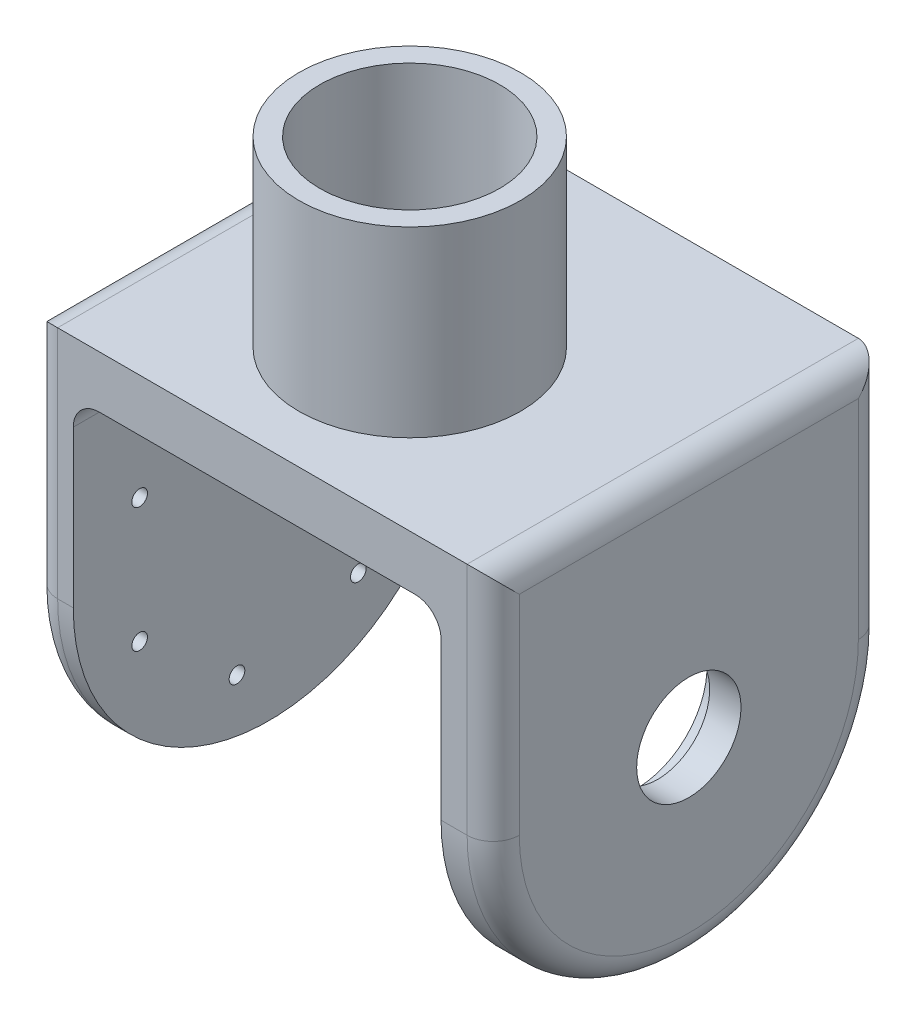
SolidWorks part; units mm, degrees
ref_plane "Alzado" through (0, 0, 0) normal (0, 0, 1) x (1, 0, 0)
ref_plane "Planta" through (0, 0, 0) normal (0, 1, 0) x (1, 0, 0)
ref_plane "Vista lateral" through (0, 0, 0) normal (1, 0, 0) x (0, 0, -1)
sketch "Croquis1" plane through (0, 0, 0) normal (1, 0, 0) x (0, 0, -1)
  line L0 (-37.5, 0) -> (-37.5, 45)
  line L1 (-37.5, 45) -> (37.5, 45)
  line L2 (37.5, 45) -> (37.5, 0)
  arc A0 (-37.5, 0) -> (37.5, 0) centre (0, 0) ccw
  circle A1 centre (27.5, 0) radius 1.5
  circle A2 centre (17.146, -21.5004) radius 1.5
  circle A3 centre (-6.1193, -26.8105) radius 1.5
  circle A4 centre (-24.7766, -11.9318) radius 1.5
  circle A5 centre (-24.7766, 11.9318) radius 1.5
  circle A6 centre (-6.1193, 26.8105) radius 1.5
  circle A7 centre (17.146, 21.5004) radius 1.5
  point P19 (0, 0)
  dimension "D1" = 75
  dimension "D2" = 3
  dimension "D3" = 27.5
  dimension "D5" = 45
  dimension "D4" = 7
extrude "Saliente-Extruir1" add sketch "Croquis1" along normal blind 8
sketch "Croquis2" plane through (0, 0, 0) normal (1, 0, 0) x (0, 0, -1)
  line L10 (37.5, 0) -> (37.5, 45) construction
  line L11 (-37.5, 45) -> (37.5, 45)
  line L12 (-37.5, 45) -> (-37.5, 35)
  line L13 (-37.5, 35) -> (37.5, 35)
  line L14 (37.5, 45) -> (37.5, 35)
  dimension "D1" = 10
extrude "Saliente-Extruir2" add sketch "Croquis2" along normal blind 78.5
ref_plane "Plano1" through (0, 80, 0) normal (0, 1, 0) x (1, 0, 0)
sketch "Croquis6" plane through (0, 80, 0) normal (0, 1, 0) x (1, 0, 0)
  circle A0 centre (42, 0) radius 6 construction
  circle A1 centre (42, -7) radius 17.25
  circle A2 centre (42, -7) radius 21.25
  dimension "D1" = 12
  dimension "D2" = 34.5
  dimension "D3" = 42
  dimension "D4" = 7
  dimension "D5" = 4
extrude "Saliente-Extruir4" add sketch "Croquis6" against normal up to body separate body
sketch "Croquis7" plane through (78.5, 0, 0) normal (1, 0, 0) x (0, 0, -1)
  line L3 (-37.5, 0) -> (-37.5, 45)
  line L4 (-37.5, 45) -> (37.5, 45)
  line L5 (37.5, 45) -> (37.5, 0)
  circle A3 centre (0, 0) radius 10
  arc A4 (-37.5, 0) -> (37.5, 0) centre (0, 0) ccw
  dimension "D1" = 20
  dimension "D2" = 75
  dimension "D3" = 45
extrude "Saliente-Extruir5" add sketch "Croquis7" along normal blind 10
sketch "Croquis8" plane through (78.5, 0, 0) normal (-1, 0, 0) x (0, 0, 1)
  circle A0 centre (0, 0) radius 22.5
  circle A1 centre (0, 0) radius 15
  dimension "D1" = 45
  dimension "D2" = 30
extrude "Cortar-Extruir1" cut sketch "Croquis8" against normal blind 2
sketch "Croquis9" plane through (78.5, 0, 0) normal (-1, 0, 0) x (0, 0, 1)
  circle A0 centre (0, 0) radius 13.5
  dimension "D1" = 27
extrude "Cortar-Extruir2" cut sketch "Croquis9" against normal blind 4
fillet "Redondeo1" radius 5 10 edges at (88.5, 22.5, 37.5) (88.5, 22.5, -37.5) (0, 22.5, 37.5) (0, 22.5, -37.5) (88.5, -37.5, 0) (0, -37.5, 0) (0, 45, 0) (88.5, 45, 0) (78.5, 35, 0) (8, 35, 0)
